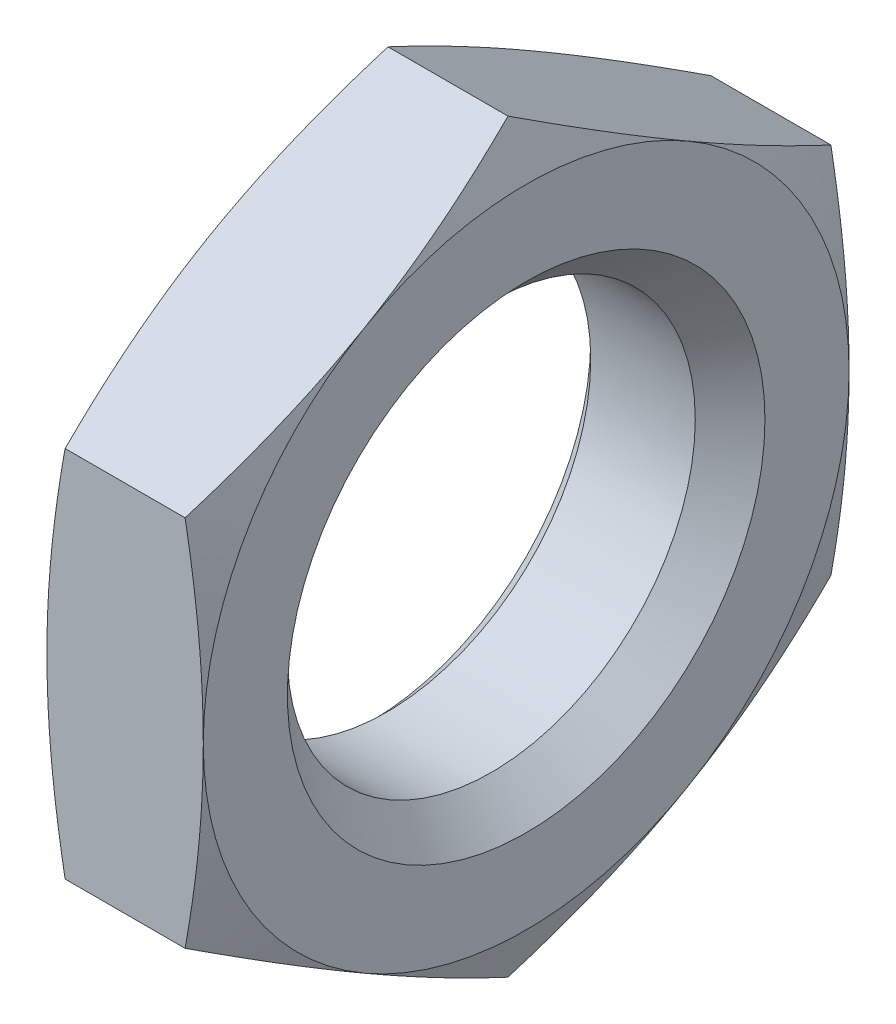
SolidWorks part; units mm, degrees
material "AISI 1020"
ref_plane "Plano superior" through (0, 0, 0) normal (0, 0, 1) x (1, 0, 0)
ref_plane "Plano frontal" through (0, 0, 0) normal (0, 1, 0) x (1, 0, 0)
ref_plane "Plano direito" through (0, 0, 0) normal (1, 0, 0) x (0, 0, -1)
sketch "Esboço1" plane through (0, 0, 0) normal (1, 0, 0) x (0, 0, -1)
  line L1 (9.5, 5.4848) -> (0, 10.9697)
  line L2 (0, 10.9697) -> (-9.5, 5.4848)
  line L3 (-9.5, 5.4848) -> (-9.5, -5.4848)
  line L4 (-9.5, -5.4848) -> (0, -10.9697)
  line L5 (0, -10.9697) -> (9.5, -5.4848)
  line L6 (9.5, -5.4848) -> (9.5, 5.4848)
  circle A0 centre (0, 0) radius 9.5 construction
  dimension "D1" = 19
extrude "Ressalto-extrusão1" add sketch "Esboço1" along normal blind 4.6
hole_wizard "Furo roscado de M141" positions "Esboço7" profile "Esboço6" tap size "M14" standard "DIN" end condition through all
sketch "Esboço7" plane through (4.6, 0, 0) normal (1, 0, 0) x (0, 0, -1)
  point P0 (0, 0)
  point P3 (0, 0)
sketch "Esboço6" plane through (4.6, 0, 0) normal (0, 1, 0) x (0, 0, -1)
  line L0 (0, 0) -> (0, 4.6)
  line L1 (0, 4.6) -> (6, 4.6)
  line L2 (6, 4.6) -> (6, 1.025)
  line L3 (6, 1.025) -> (7.025, 0)
  line L5 (7.025, 0) -> (0, 0)
  line L6 (-6, 1.025) -> (-7.025, 0) construction
  line L11 (0, -6.35) -> (0, 107.95) construction
  dimension "Thru Tap Drill Dia." = 12
  dimension "Thru Tap Drill Depth" = 4.6
  dimension "Near C'Sink Dia." = 14.05
  dimension "Near C'Sink Angle" = 90
cosmetic thread "Rosca de furo1" parameters "D2"=14
cosmetic thread "Rosca de furo2" parameters "D2"=14
chamfer "Chanfro1" distance 0.5 angle 45 1 edges at (0, 0, -6)
sketch "Esboço8" plane through (0, 0, 0) normal (-1, 0, 0) x (0, 0, 1)
  circle A0 centre (0, 0) radius 9.5
extrude "Corte-extrusão1" cut sketch "Esboço8" against normal blind 13 draft 70 flip side to cut
sketch "Esboço9" plane through (4.6, 0, 0) normal (1, 0, 0) x (0, 0, -1)
  circle A0 centre (0, 0) radius 9.5
extrude "Corte-extrusão2" cut sketch "Esboço9" against normal blind 13 draft 70 flip side to cut
